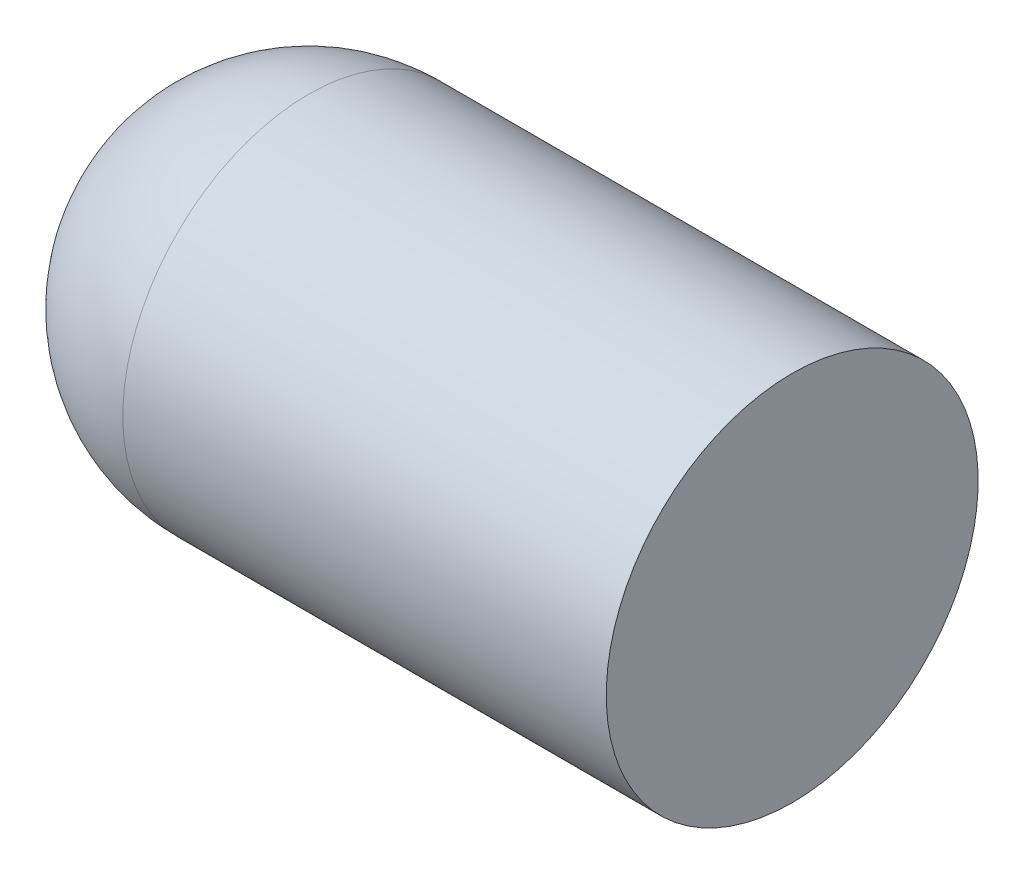
SolidWorks part; units mm, degrees
ref_plane "正面" through (0, 0, 0) normal (0, 0, 1) x (1, 0, 0)
ref_plane "平面" through (0, 0, 0) normal (0, 1, 0) x (1, 0, 0)
ref_plane "右側面" through (0, 0, 0) normal (1, 0, 0) x (0, 0, -1)
sketch "ｽｹｯﾁ1" plane through (0, 0, 0) normal (0, 0, 1) x (1, 0, 0)
  line L0 (0, 5) -> (13, 5)
  line L1 (13, 0) -> (-5, 0)
  line L2 (13, 5) -> (13, 0)
  arc A0 (-5, 0) -> (0, 5) centre (0, 0) cw
  dimension "D1" = 5
  dimension "D2" = 18
revolve "回転1" add sketch "ｽｹｯﾁ1" angle 360 about L1
